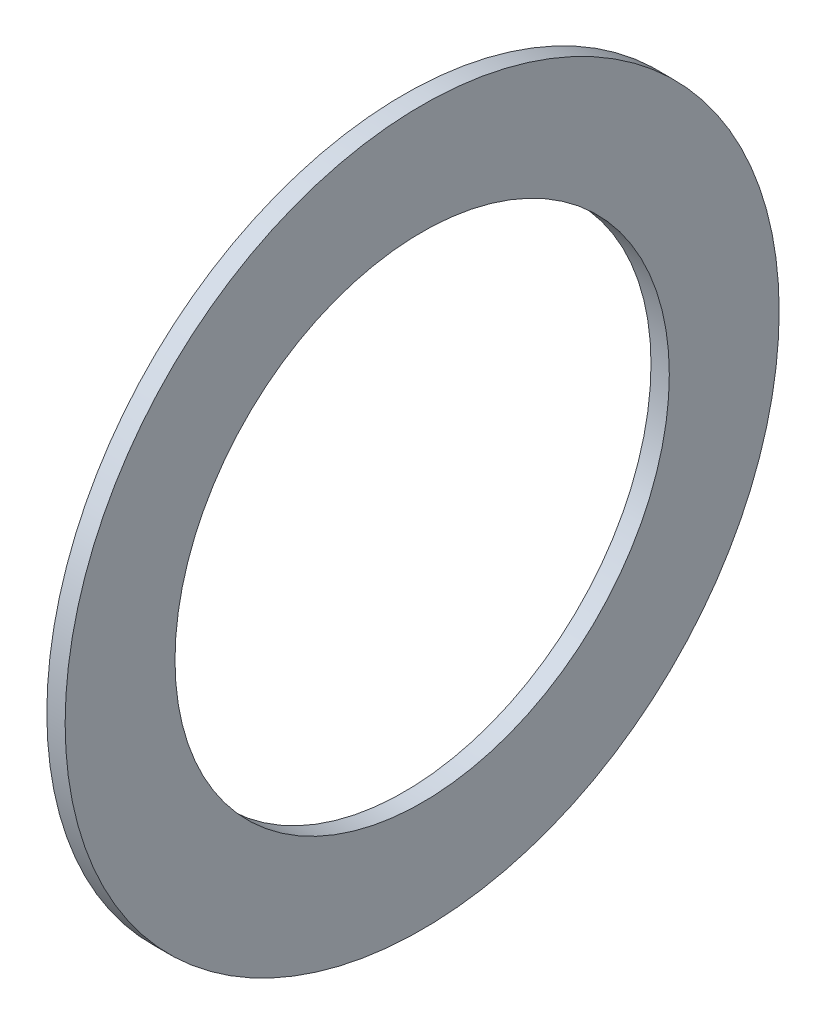
SolidWorks part; units mm, degrees
ref_plane "Front Plane" through (0, 0, 0) normal (0, 0, 1) x (1, 0, 0)
ref_plane "Top Plane" through (0, 0, 0) normal (0, 1, 0) x (1, 0, 0)
ref_plane "Right Plane" through (0, 0, 0) normal (1, 0, 0) x (0, 0, -1)
sketch "Axial profile (mm)" plane through (0, 0, 0) normal (0, 0, 1) x (1, 0, 0)
  line L0 (-110, 0) -> (75, 0) construction
  line L1 (133.7, 27) -> (135.7, 27)
  line L2 (135.7, 27) -> (135.7, 39)
  line L3 (135.7, 39) -> (133.7, 39)
  line L4 (133.7, 39) -> (133.7, 27)
revolve "Full revolution" add sketch "Axial profile (mm)" angle 360 about L0
